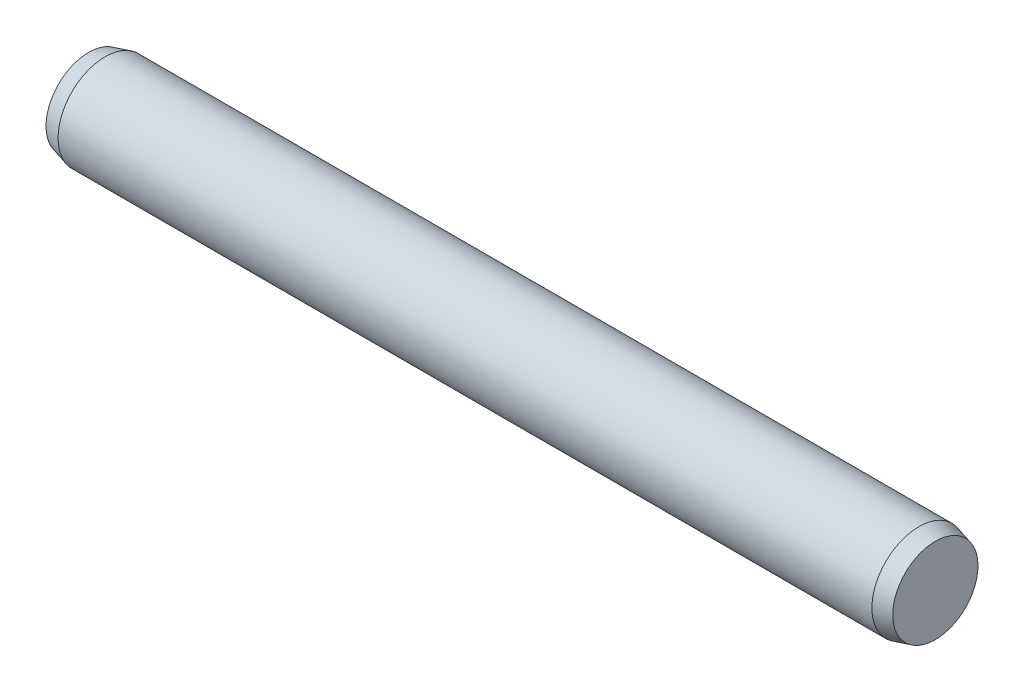
SolidWorks part; units mm, degrees
ref_plane "Front Plane" through (0, 0, 0) normal (0, 0, 1) x (1, 0, 0)
ref_plane "Top Plane" through (0, 0, 0) normal (0, 1, 0) x (1, 0, 0)
ref_plane "Right Plane" through (0, 0, 0) normal (1, 0, 0) x (0, 0, -1)
sketch "Sketch1" plane through (0, 0, 0) normal (0, 0, 1) x (1, 0, 0)
  line L0 (-8.65, 0) -> (8.65, 0) construction
  line L1 (8.65, 1) -> (8.65, -1) construction
  line L2 (-8.65, 1) -> (-8.65, -1) construction
  line L3 (9, 1) -> (9, -1) construction
  line L4 (-9, 1) -> (-9, -1) construction
  line L5 (-8.65, 0) -> (-9, 0) construction
  line L6 (8.65, 0) -> (9, 0) construction
  dimension "D1" = 0.35
  dimension "Dia" = 2
  dimension "Length" = 18
  dimension "C" = 0.35
sketch "Sketch2" plane through (0, 0, 0) normal (1, 0, 0) x (0, 0, -1)
  circle A0 centre (0, 0) radius 1
extrude "Extrude1" add sketch "Sketch2" against normal up to vertex (8.65 mm away) and the other way up to vertex (8.65 mm away) up to point (-8.65, 1, 0) other way up to point (8.65, 1, 0)
sketch "Sketch3" plane through (8.65, 0, 0) normal (1, 0, 0) x (0, 0, -1)
  circle A1 centre (0, 0) radius 1
  circle A2 centre (0, 0) radius 1
  dimension "D1" = 0
extrude "Extrude2" add sketch "Sketch3" along normal up to vertex (0.35 mm away) draft 15 up to point (9, 0, 0)
sketch "Sketch4" plane through (-8.65, 0, 0) normal (-1, 0, 0) x (0, 0, 1)
  circle A1 centre (0, 0) radius 1
  circle A2 centre (0, 0) radius 1
  dimension "D1" = 0
extrude "Extrude3" add sketch "Sketch4" along normal up to vertex (0.35 mm away) draft 15 up to point (-9, 0, 0)
equation "\"D1@Sketch1\" = \"C@Sketch1\""
